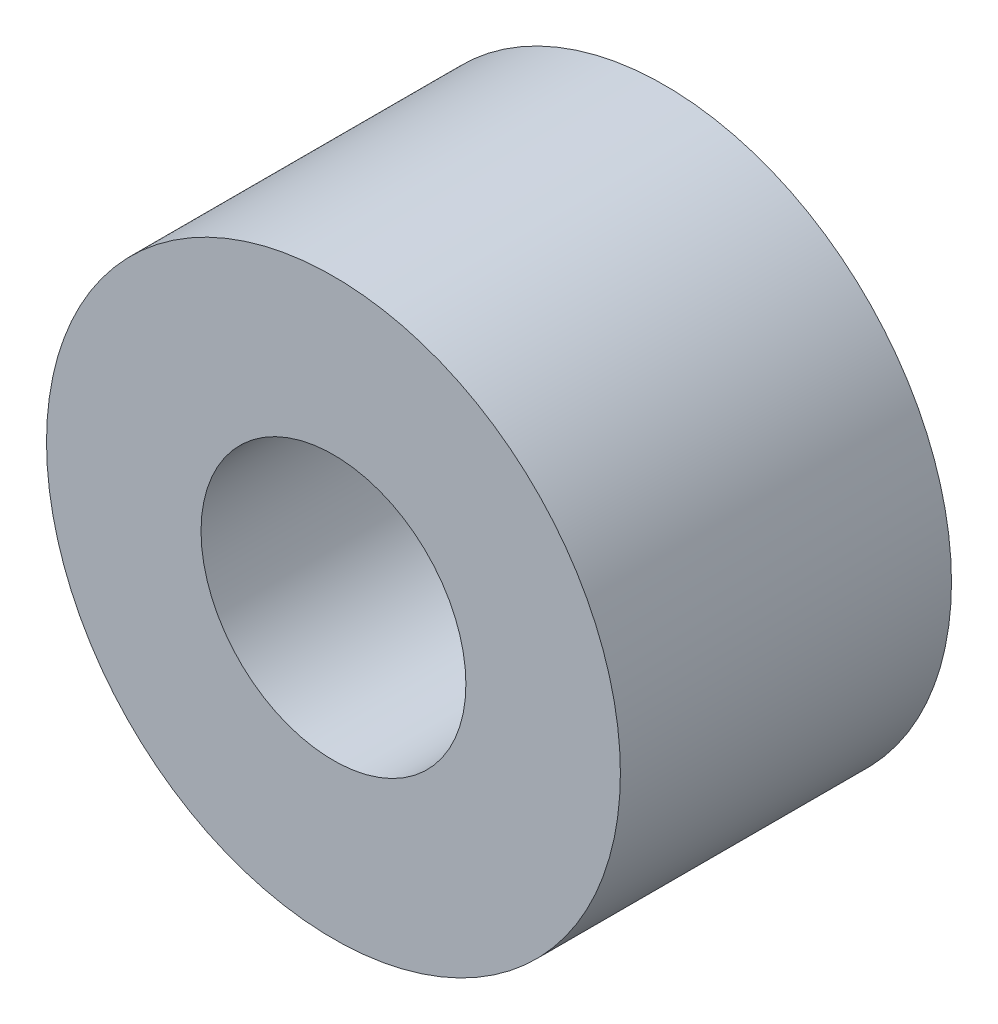
SolidWorks part; units mm, degrees
ref_plane "Front Plane" through (0, 0, 0) normal (0, 0, 1) x (1, 0, 0)
ref_plane "Top Plane" through (0, 0, 0) normal (0, 1, 0) x (1, 0, 0)
ref_plane "Right Plane" through (0, 0, 0) normal (1, 0, 0) x (0, 0, -1)
sketch "Sketch1" plane through (0, 0, 0) normal (0, 0, 1) x (1, 0, 0)
  circle A0 centre (0, 0) radius 6.5
  circle A1 centre (0, 0) radius 3
  dimension "D1" = 13
  dimension "D2" = 6
extrude "Boss-Extrude1" add sketch "Sketch1" along normal blind 7.5
equation "\"roller_radius\"= 6.5"
equation "\"eccentricity\"= \"roller_radius\" * 0.325"
equation "\"outer_radius\"= 40"
equation "\"eccentric_shaft_radius\"= 16"
equation "\"rotor_width\"= 10"
equation "\"housing_depth\"= 40"
equation "\"bottom_depth\"= 5"
equation "\"roller_bearing_OD\"= \"roller_radius\" * 2"
equation "\"roller_bearing_ID\"= 6"
equation "\"eccentric_bearing_ID\"= 6"
equation "\"eccentric_bearing_OD\"= 15"
equation "\"roller_bearing_height\"= 5"
equation "\"eccentric_bearing_height\"= 5"
equation "\"bottom_bearing_ID\"= 15"
equation "\"bottom_bearing_OD\"= 32"
equation "\"bottom_bearing_height\"= 9"
equation "\"distance_to_output_rotor_holes\"= 20"
equation "\"D1@Sketch1\"=\"roller_bearing_OD\""
equation "\"D2@Sketch1\"=\"roller_bearing_ID\""
equation "\"output_bearing_ID\" = 25"
equation "\"output_bearing_OD\" = 37"
equation "\"output_bearing_height\" = 7"
equation "\"number_of_rollers\" = 15"
equation "\"housing_height\" = 27"
equation "\"spacer_1\" = 7"
equation "\"spacer_2\" = 2.5"
equation "\"spacer_3\" = 7.5"
equation "\"roller_pin_depth\" = 5"
equation "\"D1@Boss-Extrude1\"=\"spacer_3\""
